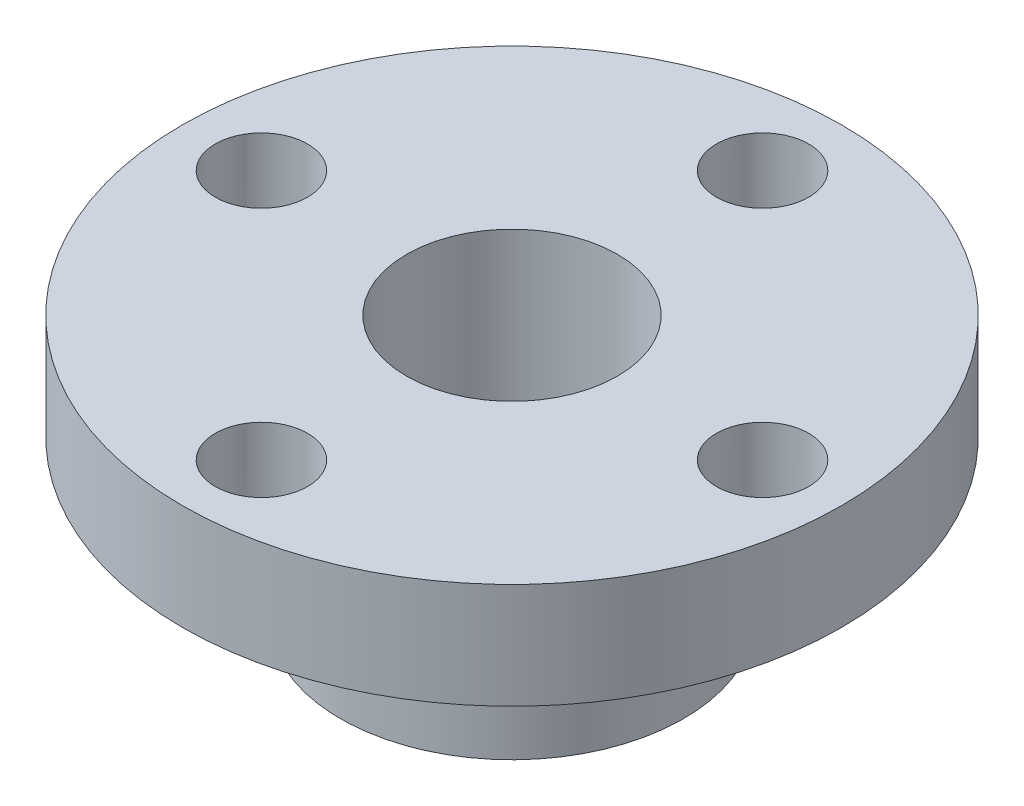
SolidWorks part; units mm, degrees
material "Delrin 2700 NC010, Low Viscosity Acetal Copolymer (SS)"
ref_plane "Front Plane" through (0, 0, 0) normal (0, 0, 1) x (1, 0, 0)
ref_plane "Top Plane" through (0, 0, 0) normal (0, 1, 0) x (1, 0, 0)
ref_plane "Right Plane" through (0, 0, 0) normal (1, 0, 0) x (0, 0, -1)
sketch "Sketch1" plane through (0, 0, 0) normal (0, 0, 1) x (1, 0, 0)
  line L0 (0, 0) -> (12.5, 0)
  line L1 (12.5, 0) -> (12.5, -4)
  line L2 (12.5, -4) -> (6.5, -4)
  line L3 (6.5, -4) -> (6.5, -10)
  line L4 (6.5, -10) -> (0, -10)
  line L5 (0, -10) -> (0, 0)
  dimension "D1" = 12.5
  dimension "D2" = 4
  dimension "D3" = 10
  dimension "D4" = 6.5
revolve "Revolve1" add sketch "Sketch1" angle 360 about L5
sketch "Sketch2" plane through (0, 0, 0) normal (0, 1, 0) x (1, 0, 0)
  line L0 (0, 0) -> (0, 12.5) construction
  circle A0 centre (0, 0) radius 4
  circle A1 centre (0, 0) radius 12.5 construction
  circle A2 centre (0, 9.5) radius 1.75
  circle A3 centre (9.5, 0) radius 1.75
  circle A4 centre (0, -9.5) radius 1.75
  circle A5 centre (-9.5, 0) radius 1.75
  point P9 (-19.4456, -1.8037)
  point P10 (0, 0)
  point P18 (0, 0)
  dimension "D1" = 3.5
  dimension "D2" = 8
  dimension "D3" = 9.5
  dimension "D4" = 4
extrude "Cut-Extrude1" cut sketch "Sketch2" against normal through all
